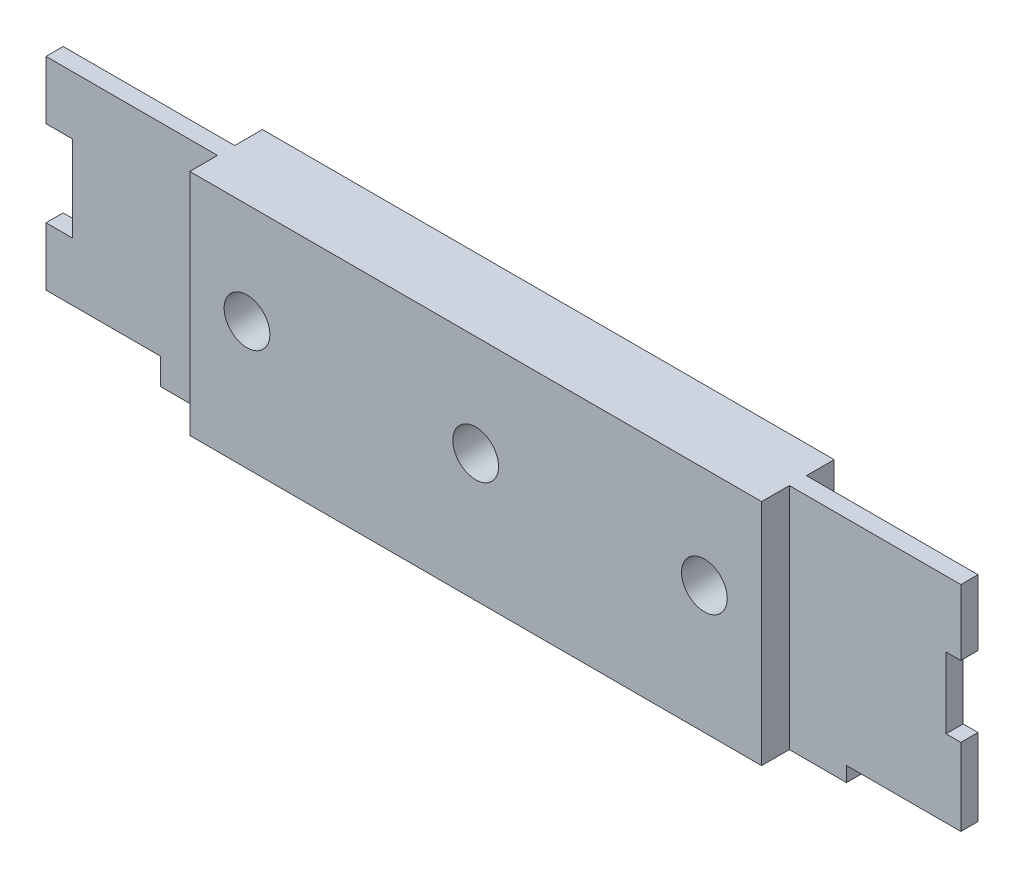
SolidWorks part; units mm, degrees
ref_plane "Alzado" through (0, 0, 0) normal (0, 0, 1) x (1, 0, 0)
ref_plane "Planta" through (0, 0, 0) normal (0, 1, 0) x (1, 0, 0)
ref_plane "Vista lateral" through (0, 0, 0) normal (1, 0, 0) x (0, 0, -1)
sketch "Croquis1" plane through (0, 0, 0) normal (0, 0, 1) x (1, 0, 0)
  line L0 (-40, 8.85) -> (40, 8.85)
  line L1 (40, 8.85) -> (40, 3.1)
  line L2 (40, 3.1) -> (38.7, 3.1)
  line L3 (38.7, 3.1) -> (38.7, -3.1)
  line L4 (38.7, -3.1) -> (40, -3.1)
  line L5 (40, -3.1) -> (40, -9.85)
  line L6 (40, -9.85) -> (30, -9.85)
  line L7 (30, -9.85) -> (30, -11.15)
  line L8 (30, -11.15) -> (-30, -11.15)
  line L9 (-30, -11.15) -> (-30, -8.85)
  line L10 (-30, -8.85) -> (-40, -8.85)
  line L11 (-40, -8.85) -> (-40, -3.75)
  line L12 (-40, -3.75) -> (-37.7, -3.75)
  line L13 (-37.7, -3.75) -> (-37.7, 3.75)
  line L14 (-37.7, 3.75) -> (-40, 3.75)
  line L15 (-40, 3.75) -> (-40, 8.85)
  line L16 (38.7, 0) -> (-37.7, 0) construction
  circle A0 centre (20, 0) radius 2
  circle A1 centre (0, 0) radius 2
  circle A2 centre (-20, 0) radius 2
  point P16 (-37.7, 0)
  point P18 (38.7, 0)
  point P19 (0, 8.85)
  dimension "D9" = 4
  dimension "D10" = 20
  dimension "D11" = 20
  dimension "D12" = 20
  dimension "D1" = 80
  dimension "D2" = 10
  dimension "D3" = 10
  dimension "D4" = 20
  dimension "D5" = 7.5
  dimension "D6" = 6.2
  dimension "D7" = 2.3
  dimension "D8" = 1.3
extrude "Saliente-Extruir1" add sketch "Croquis1" along normal mid plane 1.5
sketch "Croquis2" plane through (0, 0, 0) normal (0, 0, 1) x (1, 0, 0)
  line L0 (40, 8.85) -> (-40, 8.85) construction
  line L1 (-25, 8.85) -> (25, 8.85)
  line L2 (-25, 8.85) -> (-25, -11.15)
  line L3 (-25, -11.15) -> (25, -11.15)
  line L4 (25, 8.85) -> (25, -11.15)
  line L5 (-30, -11.15) -> (30, -11.15) construction
  line L6 (-40, 8.85) -> (-40, 3.75) construction
  line L7 (40, 3.1) -> (40, 8.85) construction
  circle A0 centre (-20, 0) radius 2
  circle A1 centre (0, 0) radius 2
  circle A2 centre (20, 0) radius 2
  dimension "D1" = 15
  dimension "D2" = 15
extrude "Saliente-Extruir2" add sketch "Croquis2" along normal mid plane 6.35
